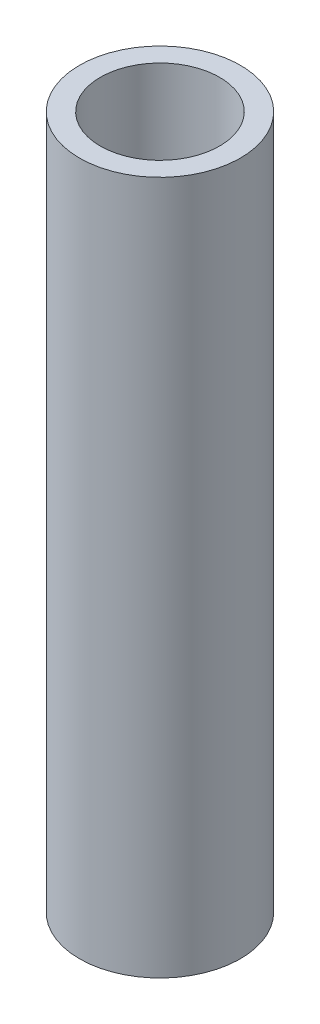
SolidWorks part; units mm, degrees
ref_plane "Front Plane" through (0, 0, 0) normal (0, 0, 1) x (1, 0, 0)
ref_plane "Top Plane" through (0, 0, 0) normal (0, 1, 0) x (1, 0, 0)
ref_plane "Right Plane" through (0, 0, 0) normal (1, 0, 0) x (0, 0, -1)
sketch "Sketch1" plane through (0, 0, 0) normal (0, 1, 0) x (1, 0, 0)
  circle A0 centre (0, 0) radius 4.3
  circle A1 centre (0, 0) radius 5.8
  dimension "D1" = 8.6
  dimension "D2" = 1.5
extrude "Boss-Extrude2" add sketch "Sketch1" along normal blind 50
